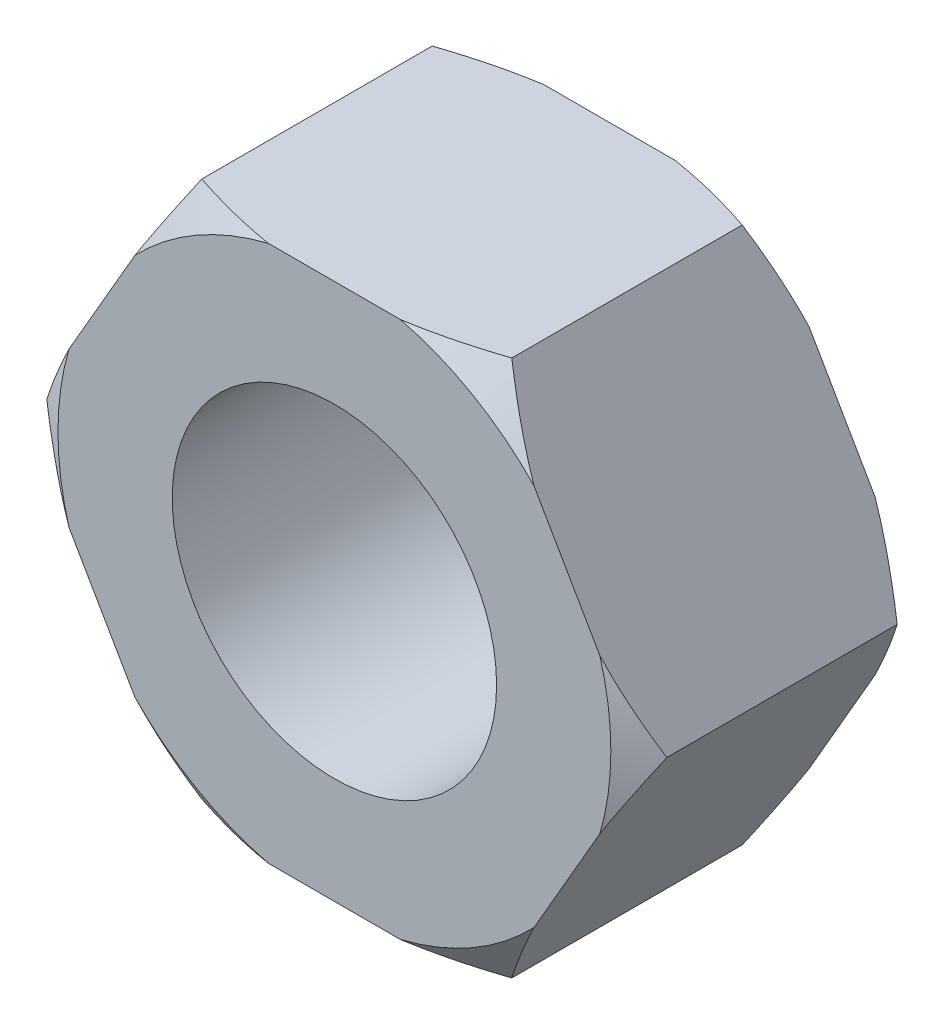
SolidWorks part; units mm, degrees
material "1.4003 (X2CrNi12)"
ref_plane "Ön Düzlem" through (0, 0, 0) normal (0, 0, 1) x (1, 0, 0)
ref_plane "Üst Düzlem" through (0, 0, 0) normal (0, 1, 0) x (1, 0, 0)
ref_plane "Sağ Düzlem" through (0, 0, 0) normal (1, 0, 0) x (0, 0, -1)
sketch "Çizim1" plane through (0, 0, 0) normal (0, 0, 1) x (1, 0, 0)
  line L1 (13.8564, 0) -> (6.9282, 12)
  line L2 (6.9282, 12) -> (-6.9282, 12)
  line L3 (-6.9282, 12) -> (-13.8564, 0)
  line L4 (-13.8564, 0) -> (-6.9282, -12)
  line L5 (-6.9282, -12) -> (6.9282, -12)
  line L6 (6.9282, -12) -> (13.8564, 0)
  circle A0 centre (0, 0) radius 12 construction
  circle A1 centre (0, 0) radius 7.25
  dimension "D1" = 24
  dimension "D2" = 14.5
extrude "Yükseklik-Ekstrüzyon1" add sketch "Çizim1" along normal blind 12.3
cosmetic thread "Kozmetik Diş Açma1" parameters "D2"=16
sketch "Çizim2" plane through (0, 0, 0) normal (0, 1, 0) x (1, 0, 0)
  line L0 (-13.8564, 0) -> (-12.3564, 0)
  line L1 (-6.9282, 0) -> (-13.8564, 0) construction
  line L2 (-12.3564, 0) -> (-13.8564, -1)
  line L3 (-13.8564, -1) -> (-13.8564, 0)
  line L4 (-13.8564, -12.3) -> (-13.8564, -11.3)
  line L5 (-13.8564, -12.3) -> (-13.8564, 0) construction
  line L6 (-13.8564, -11.3) -> (-12.3564, -12.3)
  line L7 (-6.9282, -12.3) -> (-13.8564, -12.3) construction
  line L8 (-12.3564, -12.3) -> (-13.8564, -12.3)
  line L9 (0, 0) -> (0, -12.3) construction
  line L10 (6.9282, -12.3) -> (-6.9282, -12.3) construction
  dimension "D1" = 1.5
  dimension "D2" = 1
  dimension "D3" = 1.5
  dimension "D4" = 1
revolve "Kes-Döndür1" cut sketch "Çizim2" angle 360 about L9
